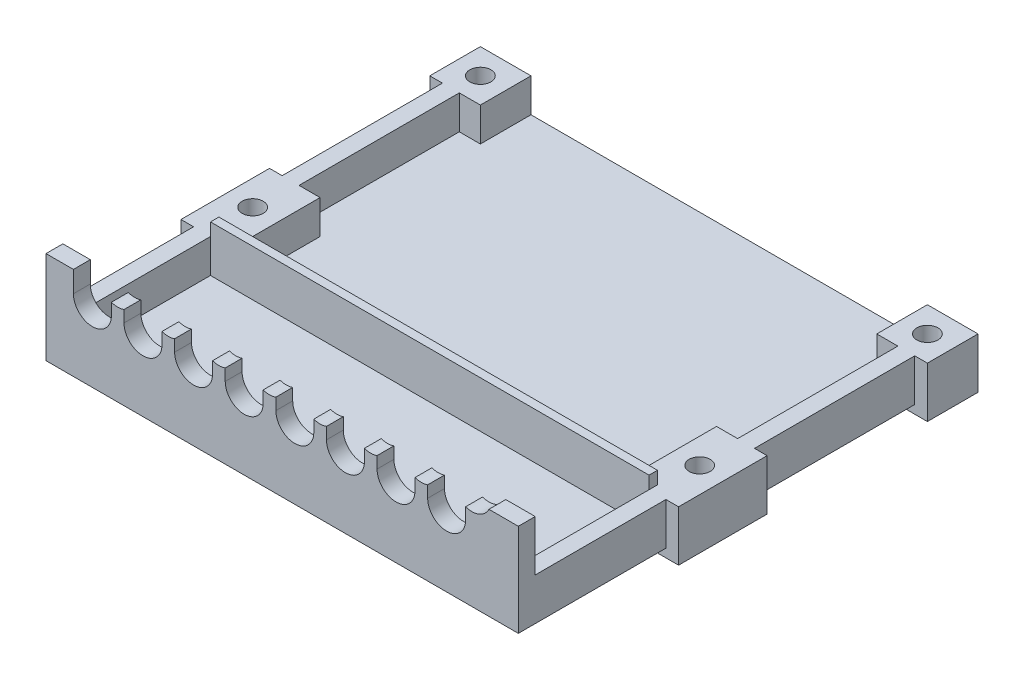
SolidWorks part; units mm, degrees
ref_plane "Front Plane" through (0, 0, 0) normal (0, 0, 1) x (1, 0, 0)
ref_plane "Top Plane" through (0, 0, 0) normal (0, 1, 0) x (1, 0, 0)
ref_plane "Right Plane" through (0, 0, 0) normal (1, 0, 0) x (0, 0, -1)
sketch "Sketch1" plane through (0, 0, 0) normal (0, 1, 0) x (1, 0, 0)
  line L1 (-28, 26.5) -> (28, 26.5)
  line L2 (-28, 26.5) -> (-28, -26.5)
  line L3 (-28, -26.5) -> (28, -26.5)
  line L4 (28, 26.5) -> (28, -26.5)
  line L5 (-28, 26.5) -> (28, -26.5) construction
  line L6 (-28, -26.5) -> (28, 26.5) construction
  point P0 (0, 0)
  dimension "D1" = 56
  dimension "D2" = 53
extrude "Boss-Extrude1" add sketch "Sketch1" along normal blind 2
sketch "Sketch2" plane through (0, 2, 0) normal (0, 1, 0) x (1, 0, 0)
  line L0 (-28, -26.5) -> (28, -26.5) construction
  line L1 (-28, 26.5) -> (-26, 26.5)
  line L2 (-28, 26.5) -> (-28, -26.5)
  line L3 (-28, -26.5) -> (-26, -26.5)
  line L4 (-26, 26.5) -> (-26, -24.5)
  line L6 (28, 26.5) -> (26, 26.5)
  line L7 (28, 26.5) -> (28, -26.5)
  line L8 (28, -26.5) -> (26, -26.5)
  line L9 (26, 26.5) -> (26, -24.5)
  line L10 (-26, -24.5) -> (26, -24.5)
  line L11 (-28, -23) -> (-28, -26.5)
  line L12 (-28, -26.5) -> (28, -26.5)
  line L13 (28, -23) -> (28, -26.5)
  line M1 (28, -26.5) -> (28, 26.5)
  line M2 (28, 26.5) -> (-28, 26.5)
  line M3 (-28, 26.5) -> (-28, -26.5)
  line M4 (-28, -26.5) -> (28, -26.5)
  dimension "D1" = 2
  dimension "D2" = 2
  dimension "D3" = 2
extrude "Boss-Extrude2" add sketch "Sketch2" along normal blind 4 contours L10 L4 L2 L7 L9 M2 M3 M4 M1
sketch "Sketch3" plane through (0, 6, 0) normal (0, 1, 0) x (1, 0, 0)
  line L0 (28, -26.5) -> (28, 26.5) construction
  line L1 (28, -24.5) -> (-28, -24.5)
  line L2 (28, -24.5) -> (28, -26.5)
  line L3 (28, -26.5) -> (-28, -26.5)
  line L4 (-28, -24.5) -> (-28, -26.5)
extrude "Boss-Extrude3" add sketch "Sketch3" along normal blind 6
sketch "Sketch4" plane through (0, 2, 0) normal (0, 1, 0) x (1, 0, 0)
  line L1 (-26, 26.5) -> (-23.5, 26.5)
  line L2 (-26, 26.5) -> (-26, 20.5)
  line L3 (-26, 20.5) -> (-23.5, 20.5)
  line L4 (-23.5, 26.5) -> (-23.5, 20.5)
  dimension "D1" = 6
  dimension "D2" = 2.5
extrude "Boss-Extrude4" add sketch "Sketch4" along normal blind 4
sketch "Sketch5" plane through (0, 2, 0) normal (0, 1, 0) x (1, 0, 0)
  line L1 (26, 26.5) -> (23.5, 26.5)
  line L2 (26, 26.5) -> (26, 20.5)
  line L3 (26, 20.5) -> (23.5, 20.5)
  line L4 (23.5, 26.5) -> (23.5, 20.5)
  dimension "D1" = 2.5
  dimension "D2" = 6
extrude "Boss-Extrude5" add sketch "Sketch5" along normal blind 4
sketch "Sketch6" plane through (-28, 0, 0) normal (-1, 0, 0) x (0, 0, 1)
  line L0 (-26.5, 0) -> (26.5, 0) construction
  line L1 (-26.5, 6) -> (-20.5, 6)
  line L2 (-26.5, 6) -> (-26.5, 0)
  line L3 (-26.5, 0) -> (-20.5, 0)
  line L4 (-20.5, 6) -> (-20.5, 0)
  dimension "D1" = 6
extrude "Boss-Extrude6" add sketch "Sketch6" along normal blind 1.5
sketch "Sketch7" plane through (28, 0, 0) normal (1, 0, 0) x (0, 0, -1)
  line L0 (-24.5, 6) -> (26.5, 6) construction
  line L1 (26.5, 0) -> (20.5, 0)
  line L2 (26.5, 0) -> (26.5, 6)
  line L3 (26.5, 6) -> (20.5, 6)
  line L4 (20.5, 0) -> (20.5, 6)
  dimension "D1" = 6
extrude "Boss-Extrude7" add sketch "Sketch7" along normal blind 1.5
sketch "Sketch8" plane through (26, 0, 0) normal (-1, 0, 0) x (0, 0, 1)
  line L0 (-20.5, 6) -> (24.5, 6) construction
  line L1 (0.5, 6) -> (-1.5, 6)
  line L2 (0.5, 6) -> (0.5, 2)
  line L3 (0.5, 2) -> (-1.5, 2)
  line L4 (-1.5, 6) -> (-1.5, 2)
  line L5 (-20.5, 2) -> (24.5, 2) construction
  line L6 (-20.5, 6) -> (-20.5, 2) construction
  dimension "D1" = 19
  dimension "D2" = 2
extrude "Boss-Extrude8" add sketch "Sketch8" along normal blind 2.5
sketch "Sketch9" plane through (-26, 0, 0) normal (1, 0, 0) x (0, 0, -1)
  line L0 (20.5, 6) -> (-24.5, 6) construction
  line L1 (1.5, 6) -> (-0.5, 6)
  line L2 (1.5, 6) -> (1.5, 2)
  line L3 (1.5, 2) -> (-0.5, 2)
  line L4 (-0.5, 6) -> (-0.5, 2)
  line L5 (20.5, 2) -> (-24.5, 2) construction
  line L6 (20.5, 6) -> (20.5, 2) construction
  dimension "D1" = 19
  dimension "D2" = 2
extrude "Boss-Extrude9" add sketch "Sketch9" along normal blind 2.5
sketch "Sketch10" plane through (0, 2, 0) normal (0, 1, 0) x (1, 0, 0)
  line L0 (-26, -0.5) -> (-26, -24.5) construction
  line L1 (-26, -8) -> (26, -8)
  line L2 (-26, -8) -> (-26, -9)
  line L3 (-26, -9) -> (26, -9)
  line L4 (26, -8) -> (26, -9)
  line L5 (26, -0.5) -> (26, -24.5) construction
  line L6 (23.5, -0.5) -> (26, -0.5) construction
  dimension "D1" = 7.5
  dimension "D2" = 1
extrude "Boss-Extrude10" add sketch "Sketch10" along normal blind 5.5
sketch "Sketch11" plane through (0, 0, 26.5) normal (0, 0, 1) x (1, 0, 0)
  line L0 (-28, 9.5) -> (28, 9.5) construction
  line L1 (-28, 12) -> (-28, 0) construction
  line L2 (28, 12) -> (28, 0) construction
  line L3 (-28, 0) -> (28, 0) construction
  line L4 (-28, 13) -> (14.25, 13) construction
  line L6 (-24.75, 9.5) -> (-24.75, 12)
  line L7 (-28, 12) -> (28, 12) construction
  line L8 (-20.25, 9.5) -> (-20.25, 10.8787)
  line L9 (-18.75, 9.5) -> (-18.75, 10.8787)
  line L10 (-14.25, 9.5) -> (-14.25, 10.8787)
  line L11 (-12.75, 9.5) -> (-12.75, 10.8787)
  line L12 (-8.25, 9.5) -> (-8.25, 10.8787)
  line L13 (-6.75, 9.5) -> (-6.75, 10.8787)
  line L14 (-2.25, 9.5) -> (-2.25, 10.8787)
  line L15 (-0.75, 9.5) -> (-0.75, 10.8787)
  line L16 (3.75, 9.5) -> (3.75, 10.8787)
  line L17 (5.25, 9.5) -> (5.25, 10.8787)
  line L18 (9.75, 9.5) -> (9.75, 10.8787)
  line L19 (11.25, 9.5) -> (11.25, 10.8787)
  line L20 (15.75, 9.5) -> (15.75, 10.8787)
  line L21 (17.25, 9.5) -> (17.25, 10.8787)
  line L22 (21.75, 9.5) -> (21.75, 10.8787)
  line L23 (18.75, 13) -> (20.25, 13) construction
  line L24 (24.75, 13) -> (28, 13) construction
  line L25 (24.75, 13) -> (-24.75, 12)
  arc A0 (-0.75, 9.5) -> (3.75, 9.5) centre (1.5, 9.5) ccw
  arc A1 (5.25, 9.5) -> (9.75, 9.5) centre (7.5, 9.5) ccw
  arc A2 (11.25, 9.5) -> (15.75, 9.5) centre (13.5, 9.5) ccw
  arc A3 (17.25, 9.5) -> (21.75, 9.5) centre (19.5, 9.5) ccw
  arc A4 (-6.75, 9.5) -> (-2.25, 9.5) centre (-4.5, 9.5) ccw
  arc A5 (-12.75, 9.5) -> (-8.25, 9.5) centre (-10.5, 9.5) ccw
  arc A6 (-18.75, 9.5) -> (-14.25, 9.5) centre (-16.5, 9.5) ccw
  arc A7 (-24.75, 9.5) -> (-20.25, 9.5) centre (-22.5, 9.5) ccw
  arc A8 (21.75, 10.8787) -> (24.75, 13) centre (22.5, 13) ccw
  arc A9 (15.75, 10.8787) -> (17.25, 10.8787) centre (16.5, 13) ccw
  arc A10 (9.75, 10.8787) -> (11.25, 10.8787) centre (10.5, 13) ccw
  arc A11 (3.75, 10.8787) -> (5.25, 10.8787) centre (4.5, 13) ccw
  arc A12 (-2.25, 10.8787) -> (-0.75, 10.8787) centre (-1.5, 13) ccw
  arc A13 (-8.25, 10.8787) -> (-6.75, 10.8787) centre (-7.5, 13) ccw
  arc A14 (-14.25, 10.8787) -> (-12.75, 10.8787) centre (-13.5, 13) ccw
  arc A15 (-20.25, 10.8787) -> (-18.75, 10.8787) centre (-19.5, 13) ccw
  dimension "D2" = 4.5
  dimension "D3" = 8.5
  dimension "D4" = 4.5
  dimension "D5" = 6
  dimension "D6" = 6
  dimension "D7" = 4.5
  dimension "D8" = 4.5
  dimension "D9" = 6
  dimension "D10" = 4.5
  dimension "D11" = 6
  dimension "D12" = 4.5
  dimension "D13" = 6
  dimension "D14" = 4.5
  dimension "D15" = 6
  dimension "D16" = 4.5
  dimension "D17" = 6
  dimension "D19" = 4.5
  dimension "D20" = 5.5
  dimension "D21" = 4.5
  dimension "D22" = 6
  dimension "D23" = 4.5
  dimension "D24" = 6
  dimension "D25" = 4.5
  dimension "D26" = 6
  dimension "D27" = 6
  dimension "D28" = 4.5
  dimension "D29" = 4.5
  dimension "D30" = 6
  dimension "D31" = 4.5
  dimension "D32" = 6
  dimension "D33" = 4.5
  dimension "D34" = 6
  dimension "D1" = 9.5
  dimension "D18" = 13
extrude "Cut-Extrude1" cut sketch "Sketch11" against normal blind 5.5
sketch "Sketch12" plane through (0, 6, 0) normal (0, 1, 0) x (1, 0, 0)
  line L0 (29.5, 26.5) -> (29.5, 20.5) construction
  line L1 (29.5, 26.5) -> (23.5, 26.5) construction
  circle A0 centre (26.5, 23.5) radius 1.25
  dimension "D1" = 2.5
  dimension "D2" = 3
  dimension "D3" = 3
extrude "Cut-Extrude2" cut sketch "Sketch12" against normal blind 15.5
sketch "Sketch13" plane through (0, 6, 0) normal (0, 1, 0) x (1, 0, 0)
  line L0 (-29.5, 20.5) -> (-29.5, 26.5) construction
  line L1 (-23.5, 26.5) -> (-29.5, 26.5) construction
  circle A0 centre (-26.5, 23.5) radius 1.25
  dimension "D1" = 2.5
  dimension "D2" = 3
  dimension "D3" = 3
extrude "Cut-Extrude3" cut sketch "Sketch13" against normal blind 15.5
sketch "Sketch14" plane through (-26, 0, 0) normal (1, 0, 0) x (0, 0, -1)
  line L1 (-0.5, 6) -> (-9, 6)
  line L2 (-0.5, 6) -> (-0.5, 2)
  line L3 (-0.5, 2) -> (-9, 2)
  line L4 (-9, 6) -> (-9, 2)
extrude "Boss-Extrude11" add sketch "Sketch14" along normal blind 2.5
sketch "Sketch15" plane through (26, 0, 0) normal (-1, 0, 0) x (0, 0, 1)
  line L1 (9, 2) -> (0.5, 2)
  line L2 (9, 2) -> (9, 6)
  line L3 (9, 6) -> (0.5, 6)
  line L4 (0.5, 2) -> (0.5, 6)
extrude "Boss-Extrude12" add sketch "Sketch15" along normal blind 2.5
sketch "Sketch16" plane through (-28, 0, 0) normal (-1, 0, 0) x (0, 0, 1)
  line L0 (-20.5, 6) -> (24.5, 6) construction
  line L1 (-1.5, 6) -> (9, 6)
  line L2 (-1.5, 6) -> (-1.5, 0)
  line L3 (-1.5, 0) -> (9, 0)
  line L4 (9, 6) -> (9, 0)
  line L5 (-20.5, 0) -> (26.5, 0) construction
  line L6 (-1.5, 2) -> (-1.5, 6) construction
  line L7 (9, 6) -> (9, 2) construction
  dimension "D1" = 0
  dimension "D2" = 0
extrude "Boss-Extrude13" add sketch "Sketch16" along normal blind 1.5
sketch "Sketch17" plane through (28, 0, 0) normal (1, 0, 0) x (0, 0, -1)
  line L0 (-24.5, 6) -> (20.5, 6) construction
  line L1 (-9, 6) -> (1.5, 6)
  line L2 (-9, 6) -> (-9, 0)
  line L3 (-9, 0) -> (1.5, 0)
  line L4 (1.5, 6) -> (1.5, 0)
  line L5 (-26.5, 0) -> (20.5, 0) construction
  line L6 (-9, 6) -> (-9, 2) construction
  line L7 (1.5, 6) -> (1.5, 2) construction
  dimension "D1" = 0
  dimension "D2" = 0
extrude "Boss-Extrude14" add sketch "Sketch17" along normal blind 1.5
sketch "Sketch18" plane through (0, 6, 0) normal (0, 1, 0) x (1, 0, 0)
  line L0 (29.5, 1.5) -> (29.5, -9) construction
  line L1 (23.5, 1.5) -> (26, 1.5) construction
  circle A0 centre (26.5, -3.5) radius 1.25
  dimension "D1" = 2.5
  dimension "D2" = 3
  dimension "D3" = 5
extrude "Cut-Extrude4" cut sketch "Sketch18" against normal blind 10
sketch "Sketch19" plane through (0, 6, 0) normal (0, 1, 0) x (1, 0, 0)
  line L0 (-29.5, -9) -> (-29.5, 1.5) construction
  line L1 (-23.5, 1.5) -> (-26, 1.5) construction
  circle A0 centre (-26.5, -3.5) radius 1.25
  dimension "D1" = 2.5
  dimension "D2" = 3
  dimension "D3" = 5
extrude "Cut-Extrude5" cut sketch "Sketch19" against normal blind 10
chamfer "Chamfer4" distance 1 angle 45 3 edges at (0, 0, 26.5)
